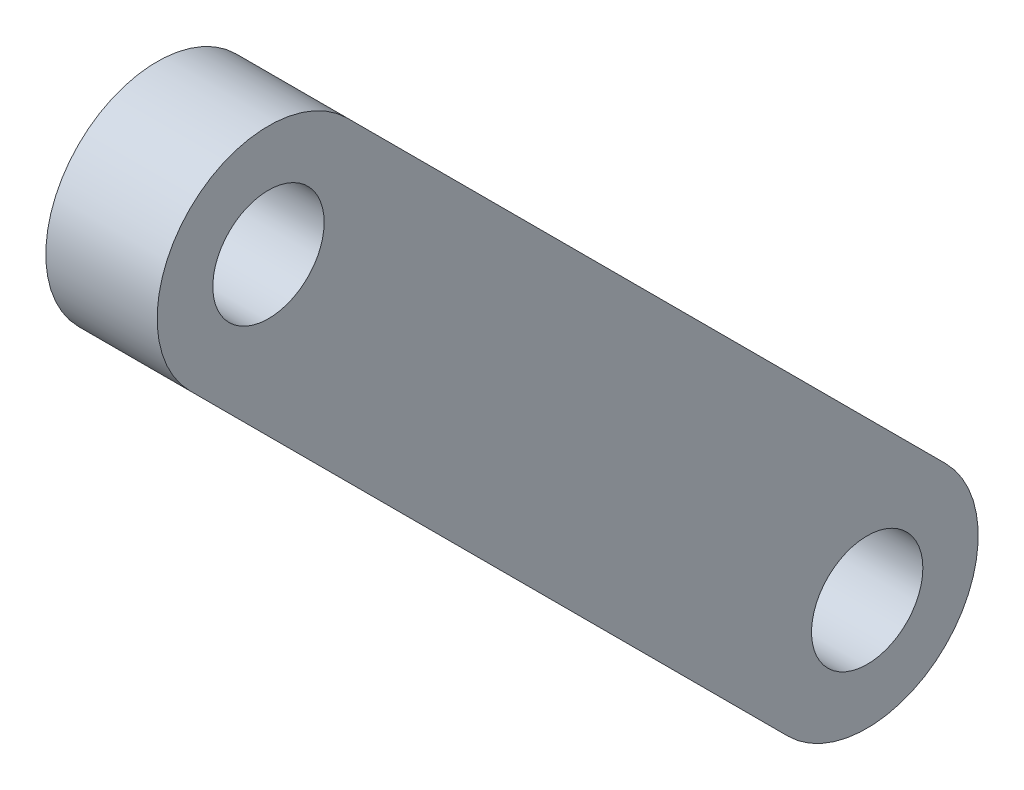
SolidWorks part; units mm, degrees
ref_plane "Front Plane" through (0, 0, 0) normal (0, 0, 1) x (1, 0, 0)
ref_plane "Top Plane" through (0, 0, 0) normal (0, 1, 0) x (1, 0, 0)
ref_plane "Right Plane" through (0, 0, 0) normal (1, 0, 0) x (0, 0, -1)
sketch "Sketch1" plane through (0, 0, 0) normal (1, 0, 0) x (0, 0, -1)
  line L0 (0, 0) -> (55.2459, 0) construction
  line L1 (0, 0) -> (10, 17.3205) construction
  line L2 (10, 17.3205) -> (59.8097, 12.9627) construction
  line L3 (59.8097, 12.9627) -> (56.3235, -26.8851) construction
  line L4 (56.3235, -26.8851) -> (29.4384, 0) construction
  line L5 (32.974, 3.5355) -> (59.844, -23.3345)
  line L6 (25.9029, -3.5355) -> (52.773, -30.4056)
  circle A0 centre (29.4384, 0) radius 2.5
  arc A1 (32.974, 3.5355) -> (25.9029, -3.5355) centre (29.4384, 0) ccw
  circle A2 centre (56.3235, -26.8851) radius 2.5
  arc A4 (59.844, -23.3345) -> (52.773, -30.4056) centre (56.3085, -26.8701) cw
  dimension "D9" = 5
  dimension "D10" = 10
  dimension "D11" = 5
  dimension "D1" = 20
  dimension "D2" = 60
  dimension "D3" = 50
  dimension "D4" = 115
  dimension "D5" = 40
  dimension "D6" = 90
  dimension "D7" = 45
  dimension "D8" = 38.0212
  dimension "D13" = 38
extrude "Boss-Extrude1" add sketch "Sketch1" along normal blind 5
